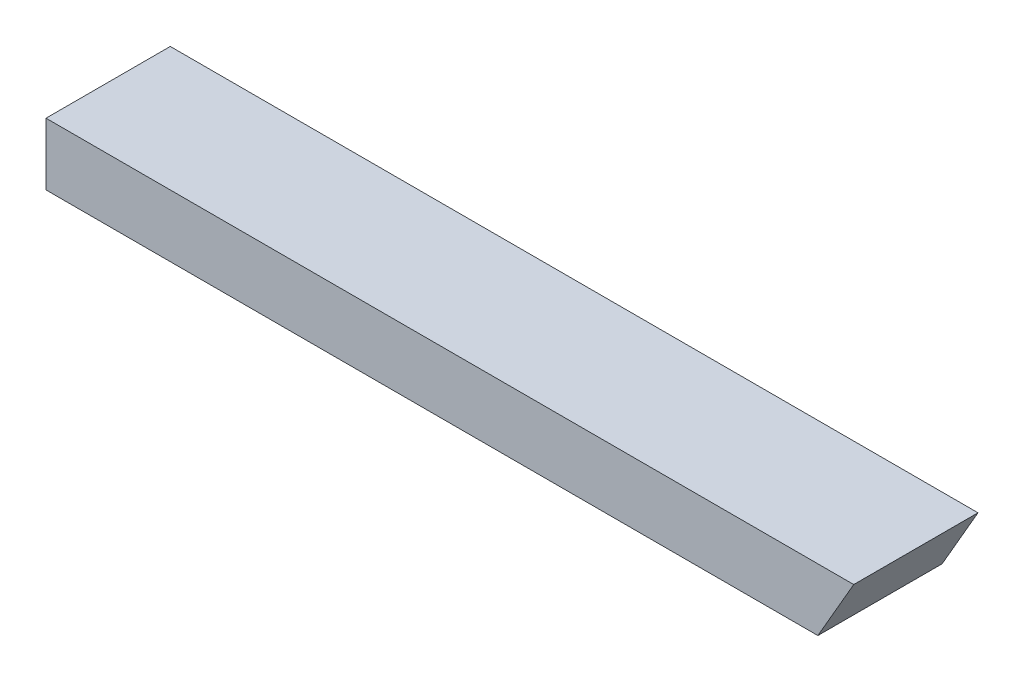
SolidWorks part; units mm, degrees
material "Thornel Mat VMA"
ref_plane "Front Plane" through (0, 0, 0) normal (0, 0, 1) x (1, 0, 0)
ref_plane "Top Plane" through (0, 0, 0) normal (0, 1, 0) x (1, 0, 0)
ref_plane "Right Plane" through (0, 0, 0) normal (1, 0, 0) x (0, 0, -1)
sketch "Sketch1" plane through (0, 0, 0) normal (0, 1, 0) x (1, 0, 0)
  line L1 (-41.275, -6.35) -> (41.275, -6.35)
  line L2 (-41.275, -6.35) -> (-41.275, 6.35)
  line L3 (-41.275, 6.35) -> (41.275, 6.35)
  line L4 (41.275, -6.35) -> (41.275, 6.35)
  line L5 (-41.275, -6.35) -> (41.275, 6.35) construction
  line L6 (-41.275, 6.35) -> (41.275, -6.35) construction
  point P0 (0, 0)
  dimension "D1" = 82.55
  dimension "D2" = 12.7
extrude "Boss-Extrude1" add sketch "Sketch1" along normal mid plane 6.35
sketch "Sketch2" plane through (0, 0, 6.35) normal (0, 0, 1) x (1, 0, 0)
  line L0 (41.275, 3.175) -> (37.6088, -3.175)
  line L1 (-41.275, -3.175) -> (41.275, -3.175) construction
  line L2 (41.275, 3.175) -> (41.275, -3.175)
  line L3 (41.275, -3.175) -> (37.6088, -3.175)
  dimension "D1" = 30
extrude "Cut-Extrude1" cut sketch "Sketch2" against normal mid plane 62.23
